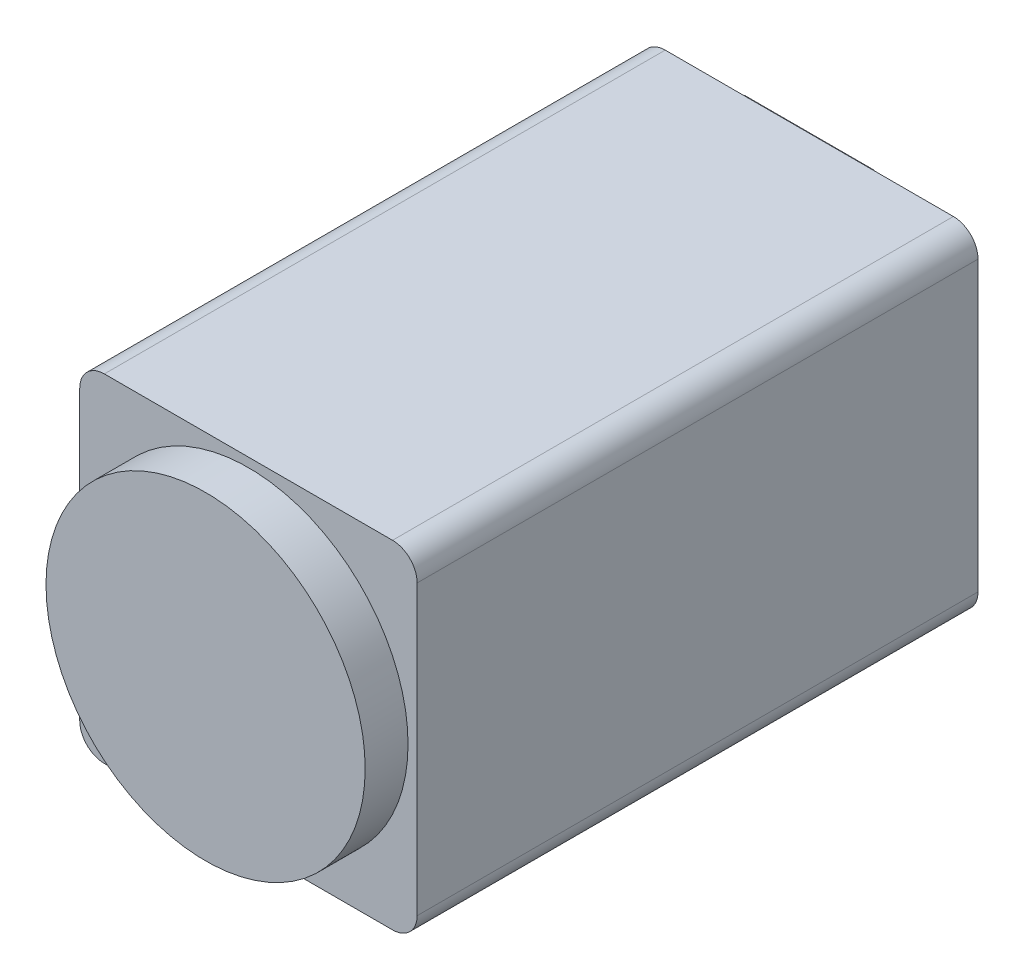
SolidWorks part; units mm, degrees
ref_plane "Front Plane" through (0, 0, 0) normal (0, 0, 1) x (1, 0, 0)
ref_plane "Top Plane" through (0, 0, 0) normal (0, 1, 0) x (1, 0, 0)
ref_plane "Right Plane" through (0, 0, 0) normal (1, 0, 0) x (0, 0, -1)
sketch "Sketch1" plane through (0, 0, 0) normal (0, 0, 1) x (1, 0, 0)
  line L1 (2.7, 0) -> (34.3, 0)
  line L2 (0, 2.7) -> (0, 34.3)
  line L3 (2.7, 37) -> (34.3, 37)
  line L4 (37, 2.7) -> (37, 34.3)
  arc A0 (2.7, 37) -> (0, 34.3) centre (2.7, 34.3) ccw
  arc A1 (37, 34.3) -> (34.3, 37) centre (34.3, 34.3) ccw
  arc A2 (34.3, 0) -> (37, 2.7) centre (34.3, 2.7) ccw
  arc A3 (2.7, 0) -> (0, 2.7) centre (2.7, 2.7) cw
  point P13 (0, 0)
  dimension "D1" = 2.7
  dimension "D2" = 2.7
  dimension "D3" = 2.7
  dimension "D4" = 2.7
extrude "Boss-Extrude1" add sketch "Sketch1" along normal blind 61.5 contours L1 A2 L4 A1 L3 A0 L2 A3
sketch "Sketch3" plane through (0, 0, 61.5) normal (0, 0, 1) x (1, 0, 0)
  circle A4 centre (18.5, 18.5) radius 17.5
  point P12 (33.4366, 9.774)
extrude "Boss-Extrude2" add sketch "Sketch3" along normal blind 4.7 contours A4
sketch "Sketch4" plane through (0, 0, 0) normal (0, 0, -1) x (-1, 0, 0)
  line L1 (-19.309, 15.2032) -> (-5.0809, 15.2032)
  line L2 (-19.309, 15.2032) -> (-19.309, 30.7563)
  line L3 (-19.309, 30.7563) -> (-5.0809, 30.7563)
  line L4 (-5.0809, 15.2032) -> (-5.0809, 30.7563)
extrude "Boss-Extrude3" add sketch "Sketch4" along normal blind 6.3 contours L2 L1 L4 L3
